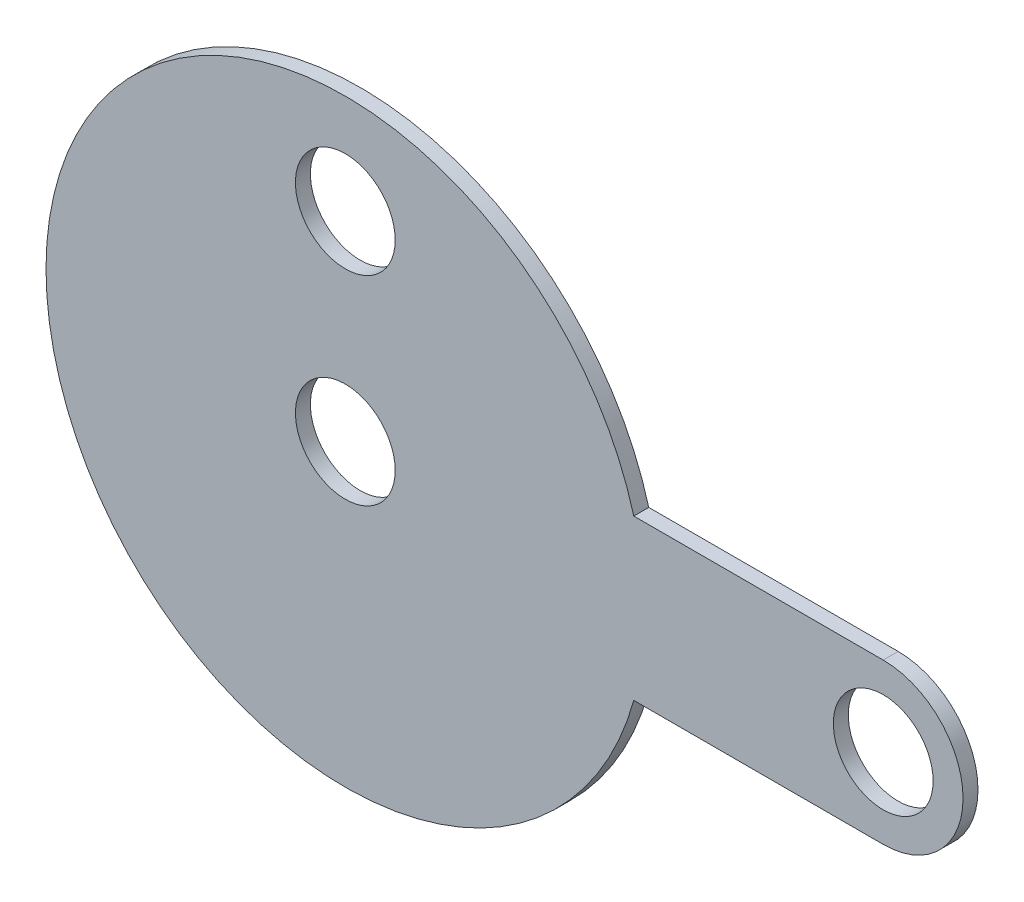
SolidWorks part; units mm, degrees
ref_plane "Front Plane" through (0, 0, 0) normal (0, 0, 1) x (1, 0, 0)
ref_plane "Top Plane" through (0, 0, 0) normal (0, 1, 0) x (1, 0, 0)
ref_plane "Right Plane" through (0, 0, 0) normal (1, 0, 0) x (0, 0, -1)
sketch "Sketch1" plane through (0, 0, 0) normal (0, 0, 1) x (1, 0, 0)
  line L0 (28.9137, 0) -> (53.9137, 0) construction
  line L1 (28.9137, 8) -> (53.9137, 8)
  line L2 (28.9137, -8) -> (53.9137, -8)
  line L3 (0, 0) -> (12.4872, 0) construction
  line L4 (0, 0) -> (0, 30) construction
  arc A0 (28.9137, 8) -> (28.9137, -8) centre (0, 0) ccw
  arc A2 (53.9137, -8) -> (53.9137, 8) centre (53.9137, 0) ccw
  circle A3 centre (0, 0) radius 5
  circle A4 centre (53.9137, 0) radius 5
  circle A5 centre (0, 20) radius 5
  point P4 (50, -1.1537)
  dimension "D1" = 60
  dimension "D3" = 25
  dimension "D4" = 8
  dimension "D7" = 20
  dimension "D8" = 10
  dimension "D9" = 10
  dimension "D10" = 10
  dimension "D2" = 16
  dimension "D5" = 25
  dimension "D6" = 25
extrude "Boss-Extrude1" add sketch "Sketch1" along normal blind 1.5
